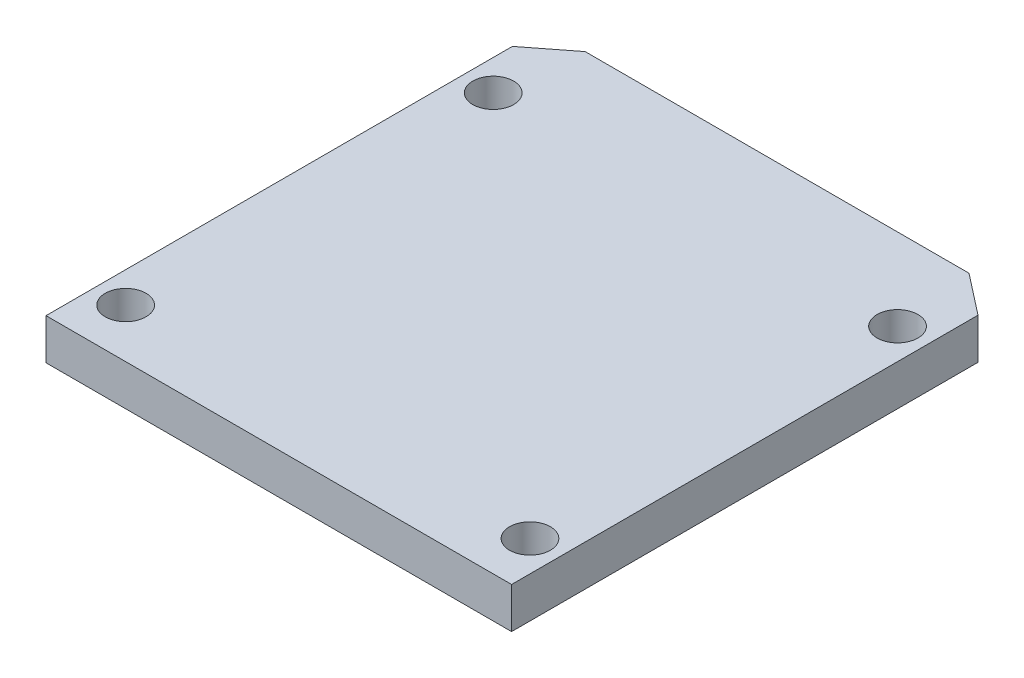
SolidWorks part; units mm, degrees
ref_plane "前视基准面" through (0, 0, 0) normal (0, 0, 1) x (1, 0, 0)
ref_plane "上视基准面" through (0, 0, 0) normal (0, 1, 0) x (1, 0, 0)
ref_plane "右视基准面" through (0, 0, 0) normal (1, 0, 0) x (0, 0, -1)
sketch "Sketch1" plane through (0, 0, 0) normal (0, 1, 0) x (1, 0, 0)
  line L0 (-17.6279, 0.7901) -> (-25.1279, 0.7901) construction
  line L1 (-25.1279, 11.8901) -> (31.8721, 11.8901)
  line L2 (-25.1279, 11.8901) -> (-25.1279, -50.2099)
  line L3 (-25.1279, -50.2099) -> (31.8721, -50.2099)
  line L4 (31.8721, 11.8901) -> (31.8721, -50.2099)
  line L5 (-17.6279, 6.8901) -> (24.3721, 6.8901)
  line L6 (-17.6279, 6.8901) -> (-17.6279, -42.7099)
  line L7 (-17.6279, -42.7099) -> (24.3721, -42.7099)
  line L8 (24.3721, 6.8901) -> (24.3721, -42.7099)
  line L9 (24.3721, 0.7901) -> (31.8721, 0.7901) construction
  circle A0 centre (-21.3779, 0.7901) radius 3.1921
  circle A1 centre (28.1221, 0.7901) radius 2.9706
  circle A2 centre (-21.3779, -44.2099) radius 1.8007
  circle A3 centre (28.1221, -44.2099) radius 1.9857
  point P20 (0, 0)
  dimension "D1" = 57
  dimension "D2" = 42
  dimension "D3" = 57.1
  dimension "D4" = 49.6
  dimension "D5" = 6.1
  dimension "D6" = 45
  dimension "D7" = 45
  dimension "D8" = 5
extrude "Boss-Extrude1" add sketch "Sketch1" along normal blind 5 contours L6 L5 L8 L7 | L2 L1 L4 L3
sketch "Sketch2" plane through (0, 0, 0) normal (0, -1, 0) x (1, 0, 0)
  line L1 (-17.6279, 42.7099) -> (24.3721, 42.7099)
  line L2 (-17.6279, 42.7099) -> (-17.6279, -6.8901)
  line L3 (-17.6279, -6.8901) -> (24.3721, -6.8901)
  line L4 (24.3721, 42.7099) -> (24.3721, -6.8901)
extrude "Boss-Extrude2" add sketch "Sketch2" against normal blind 5
sketch "Sketch5" plane through (0, 5, 0) normal (0, 1, 0) x (1, 0, 0)
  line L0 (-17.6279, 0.7901) -> (-25.1279, 0.7901) construction
  circle A0 centre (-21.3779, 0.7901) radius 4.6374
  circle A1 centre (28.1221, 0.7901) radius 6.6106
  circle A2 centre (28.1221, -44.2099) radius 7.1168
  circle A3 centre (-21.3779, -44.2099) radius 1.8038
  circle A4 centre (-21.3779, -44.2099) radius 3.75
hole_wizard "M6 Tapped Hole1" positions "3DSketch4" profile "Sketch8" tap size "M6" standard "GB" end condition through all
sketch3d "3DSketch4"
  point P0 (-21.3779, 5, -0.7901)
  point P3 (-21.3779, 5, 44.2099)
  point P6 (28.1221, 5, 44.2099)
  point P9 (28.1221, 5, -0.7901)
sketch "Sketch8" plane through (-21.3779, 5, -0.7901) normal (1, 0, 0) x (0, 0, 1)
  line L0 (0, 0) -> (0, 5)
  line L1 (0, 5) -> (2.5, 5)
  line L2 (2.5, 5) -> (2.5, 0)
  line L5 (2.5, 0) -> (0, 0)
  line L11 (0, -6.35) -> (0, 107.95) construction
  dimension "Thru Tap Drill Dia." = 5
  dimension "Thru Tap Drill Depth" = 5
cosmetic thread "Hole Thread1" parameters "D2"=6
cosmetic thread "Hole Thread2" parameters "D2"=6
cosmetic thread "Hole Thread3" parameters "D2"=6
cosmetic thread "Hole Thread4" parameters "D2"=6
sketch "Sketch9" plane through (0, 5, 0) normal (0, 1, 0) x (1, 0, 0)
  line L0 (-17.6279, 6.8901) -> (-25.1279, 6.8901)
  line L1 (-25.1279, 11.8901) -> (-25.1279, -50.2099) construction
  line L2 (-25.1279, 6.8901) -> (-20.128, 10.79)
  line L3 (-20.128, 10.79) -> (26.872, 10.7901)
  line L4 (26.872, 10.7901) -> (31.8721, 6.8901)
  line L5 (31.8721, 11.8901) -> (31.8721, -50.2099) construction
  line L6 (31.8721, 6.8901) -> (-17.6279, 6.8901)
  line L7 (-25.1279, 6.8901) -> (-25.1279, 11.8901)
  line L8 (-25.1279, 11.8901) -> (31.8721, 11.8901)
  line L9 (31.8721, 11.8901) -> (31.8721, 6.8901)
  line M11 (31.8721, -50.2099) -> (31.8721, 11.8901)
  line M12 (31.8721, 11.8901) -> (-25.1279, 11.8901)
  line M13 (-25.1279, 11.8901) -> (-25.1279, -50.2099)
  dimension "D1" = 37.954
  dimension "D2" = 37.954
  dimension "D3" = 47
  dimension "D4" = 6.341
extrude "Cut-Extrude1" cut sketch "Sketch9" against normal blind 5 contours L3 L4 L2 M11 M12 M13
